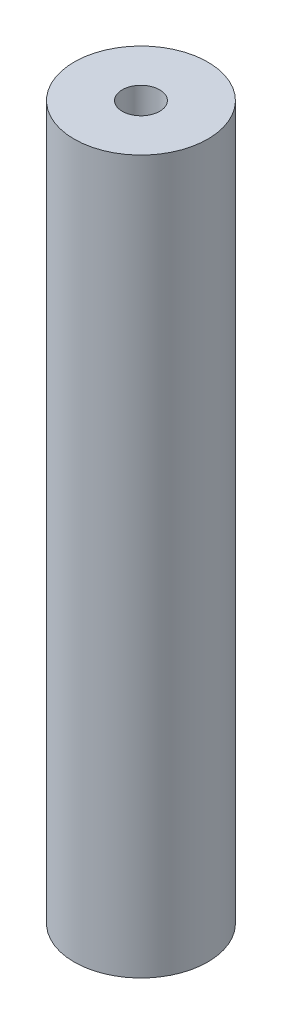
SolidWorks part; units mm, degrees
ref_plane "Front" through (0, 0, 0) normal (0, 0, 1) x (1, 0, 0)
ref_plane "Top" through (0, 0, 0) normal (0, 1, 0) x (1, 0, 0)
ref_plane "Right" through (0, 0, 0) normal (1, 0, 0) x (0, 0, -1)
sketch "Sketch1" plane through (0, 0, 0) normal (0, 1, 0) x (1, 0, 0)
  circle A0 centre (0, 0) radius 2.1
  circle A1 centre (0, 0) radius 7.5
  dimension "D1" = 4.2
  dimension "D2" = 15
extrude "Boss-Extrude1" add sketch "Sketch1" along normal blind 80
